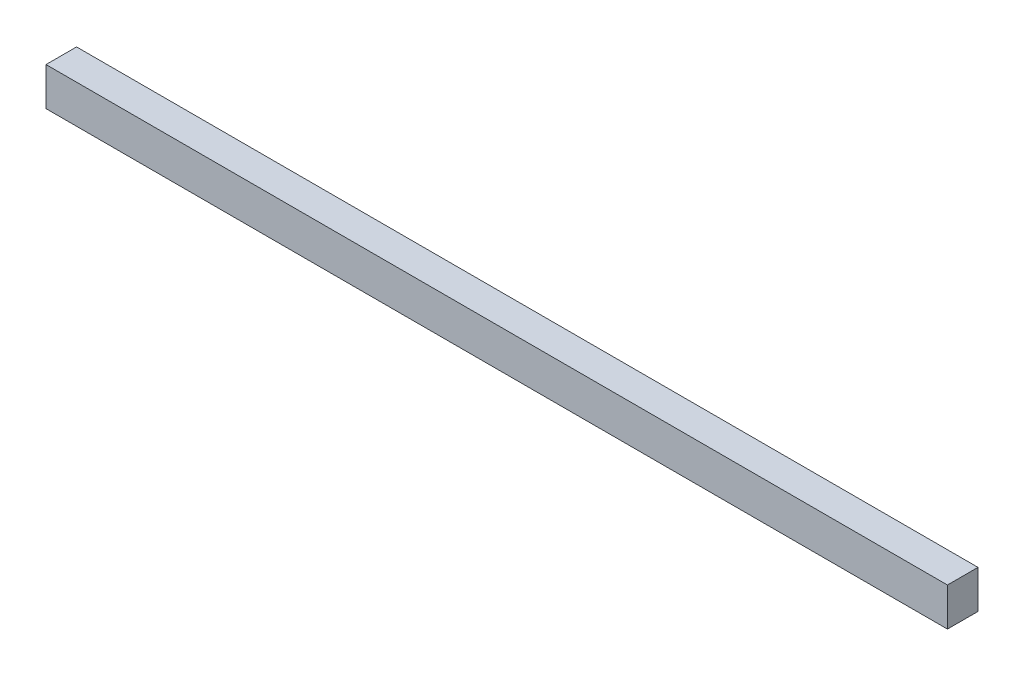
SolidWorks part; units mm, degrees
ref_plane "Front Plane" through (0, 0, 0) normal (0, 0, 1) x (1, 0, 0)
ref_plane "Top Plane" through (0, 0, 0) normal (0, 1, 0) x (1, 0, 0)
ref_plane "Right Plane" through (0, 0, 0) normal (1, 0, 0) x (0, 0, -1)
other "Configuration Table"
sketch "Sketch1" plane through (0, 0, 0) normal (0, 0, 1) x (1, 0, 0)
  line L1 (25, 255) -> (615, 255)
  line L2 (25, 255) -> (25, 280)
  line L3 (25, 280) -> (615, 280)
  line L4 (615, 255) -> (615, 280)
extrude "FKAP_cerceve_ust_1" add sketch "Sketch1" along normal blind 20 from offset 20 separate body
